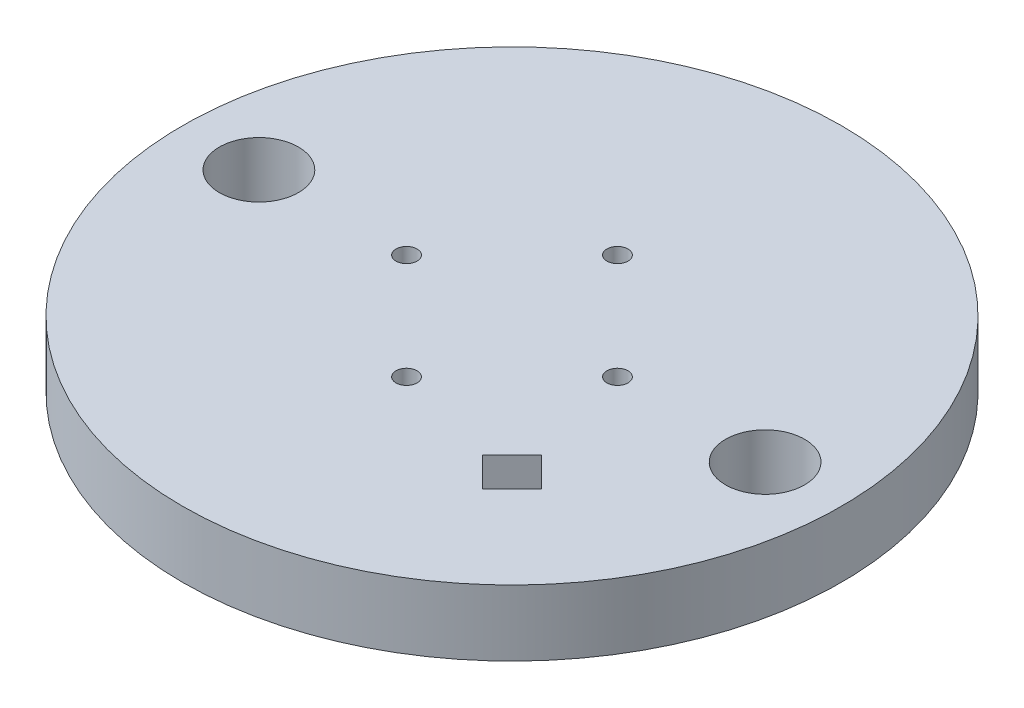
SolidWorks part; units mm, degrees
ref_plane "Front Plane" through (0, 0, 0) normal (0, 0, 1) x (1, 0, 0)
ref_plane "Top Plane" through (0, 0, 0) normal (0, 1, 0) x (1, 0, 0)
ref_plane "Right Plane" through (0, 0, 0) normal (1, 0, 0) x (0, 0, -1)
sketch "Sketch1" plane through (0, 0, 0) normal (0, 1, 0) x (1, 0, 0)
  line L0 (0, 0) -> (2.8991, -2.8991) construction
  line L1 (3.2527, -2.5456) -> (3.9598, -3.2527)
  line L2 (3.2527, -2.5456) -> (2.5456, -3.2527)
  line L3 (2.5456, -3.2527) -> (3.2527, -3.9598)
  line L4 (3.9598, -3.2527) -> (3.2527, -3.9598)
  circle A0 centre (0, 0) radius 7.9375
  circle A1 centre (-6.096, 0) radius 0.9525
  circle A2 centre (6.096, 0) radius 0.9525
  circle A3 centre (0, 2.54) radius 0.254
  circle A4 centre (-2.54, 0) radius 0.254
  circle A5 centre (0, -2.54) radius 0.254
  circle A6 centre (2.54, 0) radius 0.254
  circle A7 centre (0, 0) radius 2.54 construction
  circle A8 centre (0, 0) radius 4.1 construction
  circle A9 centre (0, 0) radius 6.096 construction
  dimension "D1" = 15.875
  dimension "D2" = 0.508
  dimension "D3" = 8.2
  dimension "D4" = 5.08
  dimension "D5" = 12.192
  dimension "D6" = 1.905
  dimension "D7" = 1
  dimension "D8" = 45
extrude "Boss-Extrude1" add sketch "Sketch1" along normal blind 1.5875
